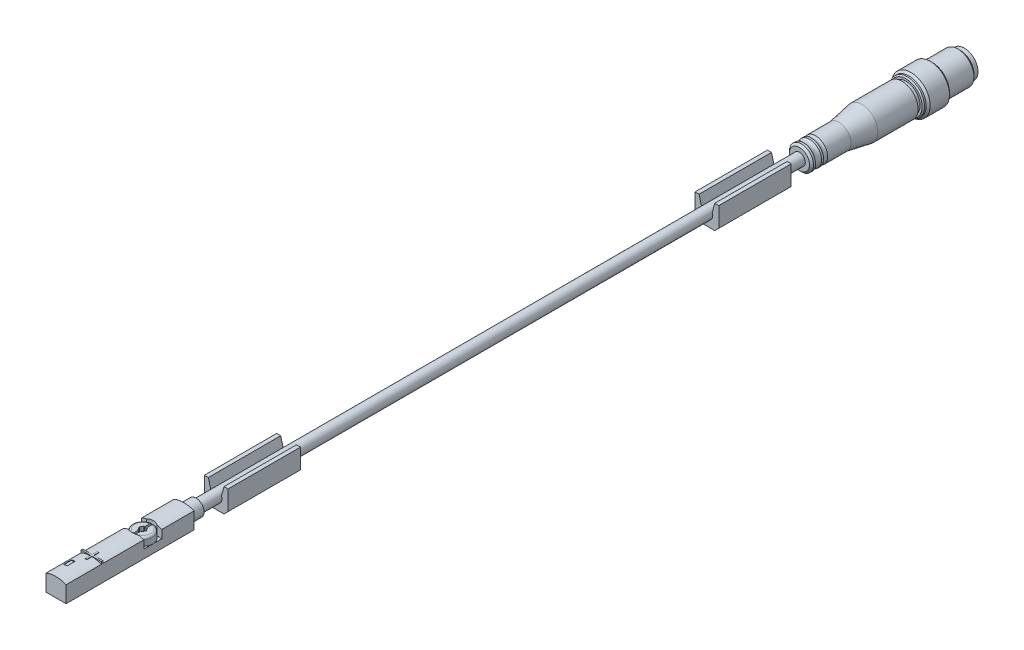
SolidWorks part; units mm, degrees
material "V2a"
ref_plane "Vorne" through (0, 0, 0) normal (0, 0, 1) x (1, 0, 0)
ref_plane "Oben" through (0, 0, 0) normal (0, 1, 0) x (1, 0, 0)
ref_plane "Rechts" through (0, 0, 0) normal (1, 0, 0) x (0, 0, -1)
ref_plane "Ebene1" through (0, 0, 0) normal (0, 0, 1) x (1, 0, 0)
sketch "Skizze1" plane through (0, 0, 0) normal (0, 0, 1) x (1, 0, 0)
  line L0 (-2.5, -2.1) -> (2.5, -2.1)
  line L1 (2.5, -2.1) -> (2.5, 2)
  line L2 (-2.5, 2) -> (-2.5, -2.1)
  arc A0 (2.5, 2) -> (-2.5, 2) centre (0, -4) ccw
extrude "Linear austragen1" add sketch "Skizze1" along normal blind 31.8
ref_plane "Ebene2" through (0, 0, 0) normal (1, 0, 0) x (0, 0, -1)
sketch "Skizze2" plane through (0, 0, 0) normal (1, 0, 0) x (0, 0, -1)
  line L0 (0, 0) -> (0, 2)
  line L1 (0, 2) -> (3, 2)
  line L2 (3, 2) -> (3, 0)
  line L3 (3, 0) -> (0, 0)
  line L4 (3, 0) -> (0, 0) construction
revolve "Rotation1" add sketch "Skizze2" angle 360 about L4
ref_plane "Ebene3" through (0, 2.6, 0) normal (0, 1, 0) x (-1, 0, 0)
sketch "Skizze3" plane through (0, 2.6, 0) normal (0, 1, 0) x (-1, 0, 0)
  line L0 (2.5, 23.05) -> (0.2, 23.05)
  line L1 (0.2, 23.05) -> (0.2, 24.35)
  line L2 (0.2, 24.35) -> (-0.2, 24.35)
  line L3 (-0.2, 24.35) -> (-0.2, 23.05)
  line L4 (-0.2, 23.05) -> (-2.5, 23.05)
  line L5 (-2.5, 23.05) -> (-2.5, 22.65)
  line L6 (-2.5, 22.65) -> (-0.2, 22.65)
  line L7 (-0.2, 22.65) -> (-0.2, 21.35)
  line L8 (-0.2, 21.35) -> (0.2, 21.35)
  line L9 (0.2, 21.35) -> (0.2, 22.65)
  line L10 (0.2, 22.65) -> (2.5, 22.65)
  line L11 (2.5, 22.65) -> (2.5, 23.05)
extrude "Linear austragen2" add sketch "Skizze3" against normal blind 2
ref_plane "Ebene4" through (0, 0, 0) normal (1, 0, 0) x (0, 0, -1)
sketch "Skizze4" plane through (0, 0, 0) normal (1, 0, 0) x (0, 0, -1)
  line L0 (3, 0) -> (3, 1.45)
  line L1 (3, 1.45) -> (153, 1.45)
  line L2 (153, 1.45) -> (153, 0)
  line L3 (153, 0) -> (3, 0)
  line L4 (153, 0) -> (3, 0) construction
revolve "Rotation2" add sketch "Skizze4" angle 360 about L4
ref_plane "Ebene5" through (0, 0, -8) normal (0, 0, 1) x (1, 0, 0)
sketch "Skizze5" plane through (0, 0, -8) normal (0, 0, 1) x (1, 0, 0)
  line L0 (-2.95, 2.95) -> (-2.95, -1.95)
  line L1 (-2.95, -1.95) -> (-1.95, -2.95)
  line L2 (-1.95, -2.95) -> (1.95, -2.95)
  line L3 (1.95, -2.95) -> (2.95, -1.95)
  line L4 (2.95, -1.95) -> (2.95, 2.95)
  line L5 (2.95, 2.95) -> (1.95, 2.95)
  line L6 (1.95, 2.95) -> (1.3202, 0.5996)
  line L7 (-1.3202, 0.5996) -> (-1.95, 2.95)
  line L8 (-1.95, 2.95) -> (-2.95, 2.95)
  arc A0 (1.3202, 0.5996) -> (-1.3202, 0.5996) centre (0, 0) cw
extrude "Linear austragen3" add sketch "Skizze5" against normal blind 18
ref_plane "Ebene6" through (0, 0, -148) normal (0, 0, 1) x (1, 0, 0)
sketch "Skizze6" plane through (0, 0, -148) normal (0, 0, 1) x (1, 0, 0)
  line L0 (-2.95, 2.95) -> (-2.95, -1.95)
  line L1 (-2.95, -1.95) -> (-1.95, -2.95)
  line L2 (-1.95, -2.95) -> (1.95, -2.95)
  line L3 (1.95, -2.95) -> (2.95, -1.95)
  line L4 (2.95, -1.95) -> (2.95, 2.95)
  line L5 (2.95, 2.95) -> (1.95, 2.95)
  line L6 (1.95, 2.95) -> (1.3202, 0.5996)
  line L7 (-1.3202, 0.5996) -> (-1.95, 2.95)
  line L8 (-1.95, 2.95) -> (-2.95, 2.95)
  arc A0 (1.3202, 0.5996) -> (-1.3202, 0.5996) centre (0, 0) cw
extrude "Linear austragen4" add sketch "Skizze6" along normal blind 18
ref_plane "Ebene7" through (0, 0, 0) normal (1, 0, 0) x (0, 0, -1)
sketch "Skizze7" plane through (0, 0, 0) normal (1, 0, 0) x (0, 0, -1)
  line L0 (153, 0) -> (153, 2.5)
  line L1 (153, 2.5) -> (153.5, 3)
  line L2 (153.5, 3) -> (154, 3)
  line L3 (155.5, 3) -> (156, 3)
  line L4 (157, 3) -> (162.8287, 3)
  line L5 (162.8287, 3) -> (168.5, 4)
  line L6 (168.5, 4) -> (178.5, 4)
  line L7 (178.5, 4) -> (178.5, 3.5)
  line L8 (178.5, 3.5) -> (179.5, 3.5)
  line L9 (179.5, 3.5) -> (179.5, 4)
  line L10 (179.5, 4) -> (179.8, 4.3)
  line L11 (179.8, 4.3) -> (180.2, 4.3)
  line L12 (180.2, 4.3) -> (180.7, 4.8)
  line L13 (180.7, 4.8) -> (185.5, 4.8)
  line L14 (185.5, 4.8) -> (186, 4.3)
  line L15 (186, 4.3) -> (186, 4)
  line L16 (186, 4) -> (192.3865, 4)
  line L17 (192.3865, 4) -> (193, 3.3865)
  line L18 (193, 3.3865) -> (194, 3.3865)
  line L19 (194, 3.3865) -> (194, 0)
  line L20 (194, 0) -> (153, 0)
  line L21 (194, 0) -> (153, 0) construction
  arc A0 (154, 3) -> (155.5, 3) centre (154.75, 4.299) ccw
  arc A1 (156, 3) -> (157, 3) centre (156.5, 3.866) ccw
revolve "Rotation3" add sketch "Skizze7" angle 360 about L21
ref_plane "Ebene8" through (0, 2.6, 0) normal (0, 1, 0) x (-1, 0, 0)
sketch "Skizze8" plane through (0, 2.6, 0) normal (0, 1, 0) x (-1, 0, 0)
  line L0 (2, 28) -> (1, 28)
  line L1 (1, 28) -> (1, 26)
  line L2 (1, 26) -> (2, 26)
  line L3 (2, 26) -> (2, 28)
extrude "Linear austragen5" cut sketch "Skizze8" against normal blind 0.5 and the other way blind 0.5
ref_plane "Ebene9" through (0, 2.6, 0) normal (0, 1, 0) x (-1, 0, 0)
sketch "Skizze9" plane through (0, 2.6, 0) normal (0, 1, 0) x (-1, 0, 0)
  line L0 (5, 8) -> (5, 12.5)
  line L1 (5, 12.5) -> (1.3029, 12.5)
  line L2 (-1.3029, 12.5) -> (-5, 12.5)
  line L3 (-5, 12.5) -> (-5, 8)
  line L4 (-5, 8) -> (-1.3029, 8)
  line L5 (1.3029, 8) -> (5, 8)
  arc A0 (1.3029, 12.5) -> (-1.3029, 12.5) centre (0, 10.25) ccw
  arc A1 (-1.3029, 8) -> (1.3029, 8) centre (0, 10.25) ccw
extrude "Linear austragen6" cut sketch "Skizze9" against normal blind 2.6
ref_plane "Ebene10" through (0, 0, 0) normal (1, 0, 0) x (0, 0, -1)
sketch "Skizze10" plane through (0, 0, 0) normal (1, 0, 0) x (0, 0, -1)
  line L0 (-10.25, 2) -> (-8.25, 2)
  line L1 (-7.75, 1.5) -> (-7.75, 0)
  line L2 (-7.75, 0) -> (-10.25, 0)
  line L3 (-10.25, 0) -> (-10.25, 2)
  line L4 (-10.25, 0) -> (-10.25, 2) construction
  arc A0 (-8.25, 2) -> (-7.75, 1.5) centre (-8.25, 1.5) cw
revolve "Rotation4" add sketch "Skizze10" angle 360 about L4
ref_plane "Ebene11" through (0, 2.6, 0) normal (0, 1, 0) x (-1, 0, 0)
sketch "Skizze11" plane through (0, 2.6, 0) normal (0, 1, 0) x (-1, 0, 0)
  line L0 (0.866, 10.25) -> (0.433, 11)
  line L1 (0.433, 11) -> (0.25, 11)
  line L2 (0.25, 11) -> (0.25, 12.7375)
  line L3 (-0.25, 12.7375) -> (-0.25, 11)
  line L4 (-0.25, 11) -> (-0.433, 11)
  line L5 (-0.433, 11) -> (-0.866, 10.25)
  line L6 (-0.866, 10.25) -> (-0.433, 9.5)
  line L7 (-0.433, 9.5) -> (-0.25, 9.5)
  line L8 (-0.25, 9.5) -> (-0.25, 7.7625)
  line L9 (0.25, 7.7625) -> (0.25, 9.5)
  line L10 (0.25, 9.5) -> (0.433, 9.5)
  line L11 (0.433, 9.5) -> (0.866, 10.25)
  arc A0 (0.25, 12.7375) -> (-0.25, 12.7375) centre (0, 10.25) ccw
  arc A1 (-0.25, 7.7625) -> (0.25, 7.7625) centre (0, 10.25) ccw
extrude "Linear austragen7" cut sketch "Skizze11" against normal blind 2.1
